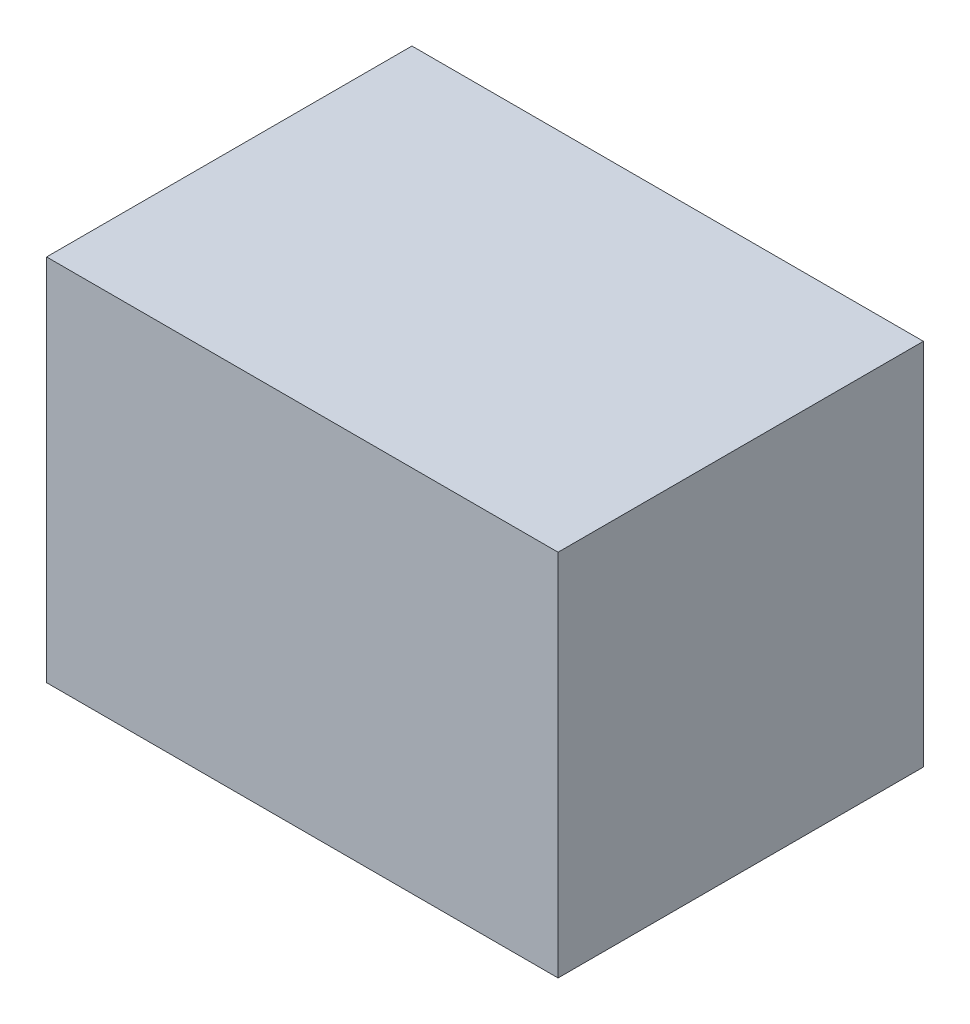
SolidWorks part; units mm, degrees
ref_plane "Front Plane" through (0, 0, 0) normal (0, 0, 1) x (1, 0, 0)
ref_plane "Top Plane" through (0, 0, 0) normal (0, 1, 0) x (1, 0, 0)
ref_plane "Right Plane" through (0, 0, 0) normal (1, 0, 0) x (0, 0, -1)
sketch "Sketch2" plane through (0, 0, 0) normal (0, 1, 0) x (1, 0, 0)
  line L1 (-52.5, 37.5) -> (52.5, 37.5)
  line L2 (-52.5, 37.5) -> (-52.5, -37.5)
  line L3 (-52.5, -37.5) -> (52.5, -37.5)
  line L4 (52.5, 37.5) -> (52.5, -37.5)
  line L5 (-52.5, 37.5) -> (52.5, -37.5) construction
  line L6 (-52.5, -37.5) -> (52.5, 37.5) construction
  point P0 (0, 0)
  dimension "D1" = 75
  dimension "D2" = 105
extrude "Boss-Extrude1" add sketch "Sketch2" along normal blind 75.7
